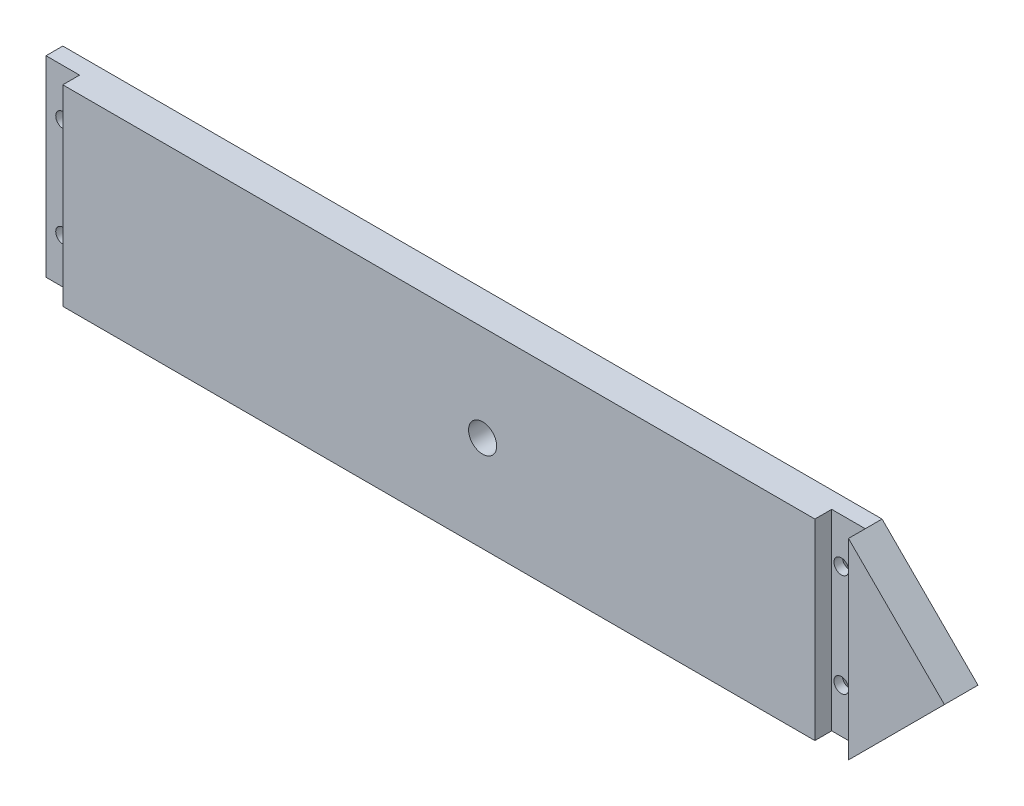
SolidWorks part; units mm, degrees
material "Brass"
ref_plane "Front Plane" through (0, 0, 0) normal (0, 0, 1) x (1, 0, 0)
ref_plane "Top Plane" through (0, 0, 0) normal (0, 1, 0) x (1, 0, 0)
ref_plane "Right Plane" through (0, 0, 0) normal (1, 0, 0) x (0, 0, -1)
sketch "Sketch1" plane through (0, 0, 0) normal (0, 0, 1) x (1, 0, 0)
  line L0 (86.5187, 18.1394) -> (-86.5187, -18.1394) construction
  line L1 (86.5187, 18.1394) -> (-86.5187, 18.1394)
  line L2 (86.5187, 18.1394) -> (86.5187, -18.1394)
  line L3 (86.5187, -18.1394) -> (-86.5187, -18.1394)
  line L4 (-86.5187, 18.1394) -> (-86.5187, -18.1394)
  line L5 (0, 67.5638) -> (0, -55.9908) construction
  line L6 (-104.9725, 0) -> (100.2455, 0) construction
  dimension "sight arm length" = 173.0375
  dimension "D2" = 36.2788
extrude "Extrude2" add sketch "Sketch1" along normal blind 6.35
sketch "Sketch8" plane through (0, 0, 6.35) normal (0, 0, 1) x (1, 0, 0)
  line L0 (-0.7937, -951.8707) -> (-0.7937, 49048.1293) construction
  line L1 (-80.1687, -1000.1415) -> (-80.1687, 48999.8585) construction
  line L2 (62.0306, -999.8068) -> (62.0306, 49000.1932) construction
  line L3 (68.3806, -999.1373) -> (68.3806, 49000.8627) construction
  line L5 (-86.5187, 18.1394) -> (-80.1687, 18.1394)
  line L6 (-80.1687, 18.1394) -> (-80.1687, -18.1394)
  line L8 (-80.1687, -18.1394) -> (-86.5187, -18.1394)
  line L9 (-86.5187, -18.1394) -> (-86.5187, 18.1394)
  line L10 (62.0306, 18.1394) -> (68.3806, 18.1394)
  line L11 (86.5187, 18.1394) -> (-86.5187, 18.1394) construction
  line L12 (68.3806, 18.1394) -> (68.3806, -18.1394)
  line L13 (68.3806, -18.1394) -> (62.0306, -18.1394)
  line L14 (-86.5187, -18.1394) -> (86.5187, -18.1394) construction
  line L15 (62.0306, -18.1394) -> (62.0306, 18.1394)
  line L17 (86.5187, -18.1394) -> (86.5187, 18.1394) construction
  dimension "D1" = 6.35
  dimension "D2" = 6.35
  dimension "D3" = 18.1381
  dimension "D4" = 173.0375
  dimension "D5" = 62.8244
  dimension "D6" = 79.375
extrude "Extrude7" cut sketch "Sketch8" against normal blind 3.175
hole_wizard "CSK for #3 Flat Head Socket Cap Screw1" positions "Sketch12" profile "Sketch13" countersink size "#3" standard "Ansi Inch" end condition through all
sketch "Sketch12" plane through (-27.7477, -5.396, 0) normal (0, 0, -1) x (-1, 0, 0)
  point P0 (55.5338, -4.331)
sketch "Sketch13" plane through (-83.2815, -9.727, 0) normal (1, 0, 0) x (0, 1, 0)
  line L0 (0, 0) -> (0, 6.35)
  line L1 (0, 6.35) -> (1.397, 6.35)
  line L2 (1.397, 6.35) -> (1.397, 1.5662)
  line L3 (1.397, 1.5662) -> (2.7584, 0)
  line L4 (2.7584, 0) -> (0, 0)
  line L5 (-1.397, 1.5662) -> (-2.7584, 0) construction
  line L6 (0, -6.35) -> (0, 107.95) construction
  dimension "Thru Hole Dia." = 2.794
  dimension "Thru Hole Depth" = 6.35
  dimension "Near C'Sink Dia." = 5.5169
  dimension "Near C'Sink Angle" = 82
hole_wizard "CSK for #3 Flat Head Socket Cap Screw2" positions "Sketch14" profile "Sketch15" countersink size "#3" standard "Ansi Inch" end condition through all
sketch "Sketch14" plane through (-27.7477, -5.396, 0) normal (0, 0, -1) x (-1, 0, 0)
  point P0 (55.5338, 14.6085)
sketch "Sketch15" plane through (-83.2815, 9.2125, 0) normal (1, 0, 0) x (0, 1, 0)
  line L0 (0, 0) -> (0, 6.35)
  line L1 (0, 6.35) -> (1.397, 6.35)
  line L2 (1.397, 6.35) -> (1.397, 1.5662)
  line L3 (1.397, 1.5662) -> (2.7584, 0)
  line L4 (2.7584, 0) -> (0, 0)
  line L5 (-1.397, 1.5662) -> (-2.7584, 0) construction
  line L6 (0, -6.35) -> (0, 107.95) construction
  dimension "Thru Hole Dia." = 2.794
  dimension "Thru Hole Depth" = 6.35
  dimension "Near C'Sink Dia." = 5.5169
  dimension "Near C'Sink Angle" = 82
hole_wizard "CSK for #3 Flat Head Socket Cap Screw3" positions "Sketch16" profile "Sketch17" countersink size "#3" standard "Ansi Inch" end condition through all
sketch "Sketch16" plane through (-27.7477, -5.396, 0) normal (0, 0, -1) x (-1, 0, 0)
  point P0 (-91.6008, -4.3183)
  point P1 (-91.6008, 15.1102)
sketch "Sketch17" plane through (63.8531, -9.7142, 0) normal (1, 0, 0) x (0, 1, 0)
  line L0 (0, 0) -> (0, 6.35)
  line L1 (0, 6.35) -> (1.397, 6.35)
  line L2 (1.397, 6.35) -> (1.397, 1.5662)
  line L3 (1.397, 1.5662) -> (2.7584, 0)
  line L5 (2.7584, 0) -> (0, 0)
  line L6 (-1.397, 1.5662) -> (-2.7584, 0) construction
  line L11 (0, -6.35) -> (0, 107.95) construction
  dimension "Thru Hole Dia." = 2.794
  dimension "Thru Hole Depth" = 6.35
  dimension "Near C'Sink Dia." = 5.5169
  dimension "Near C'Sink Angle" = 82
sketch "Sketch18" plane through (0, 0, 6.35) normal (0, 0, 1) x (1, 0, 0)
  line L0 (86.5188, -1000) -> (86.5187, 49000) construction
  line L1 (86.5187, -18.1394) -> (86.5187, 18.1394) construction
  line L2 (68.3806, -1000) -> (68.3806, 49000) construction
  line L3 (68.3806, -18.1394) -> (68.3806, 18.1394) construction
  line L4 (86.5187, 0) -> (-35267.5826, 35356.5768) construction
  line L5 (86.5187, 0) -> (-35267.5826, -35356.5768) construction
  line L6 (86.5187, 0) -> (-35267.5826, 35356.5768) construction
  line L7 (113.5192, -985.2417) -> (113.5192, 49014.7583) construction
  line L8 (86.5188, 0) -> (68.3806, 18.1394)
  line L9 (68.3806, 18.1394) -> (113.5192, 18.1394)
  line L10 (86.5188, 0) -> (68.3806, -18.1394)
  line L11 (113.5192, -18.1394) -> (113.5192, 18.1394)
  line L12 (113.5192, -18.1394) -> (68.3806, -18.1394)
  point P5 (86.5187, 0)
  point P10 (68.3806, 0)
extrude "Extrude8" cut sketch "Sketch18" against normal through all
sketch "Sketch19" plane through (0, 0, 6.35) normal (0, 0, 1) x (1, 0, 0)
  line L0 (-80.1687, -18.1394) -> (62.0306, -18.1394) construction
  line L1 (-86.5187, 18.1394) -> (-86.5187, -18.1394) construction
  circle A0 centre (-0.7937, 0) radius 2.6566
  point P2 (-9.0691, -18.1394)
  dimension "D1" = 18.1394
  dimension "D2" = 85.725
extrude "Extrude9" cut sketch "Sketch19" against normal through all
